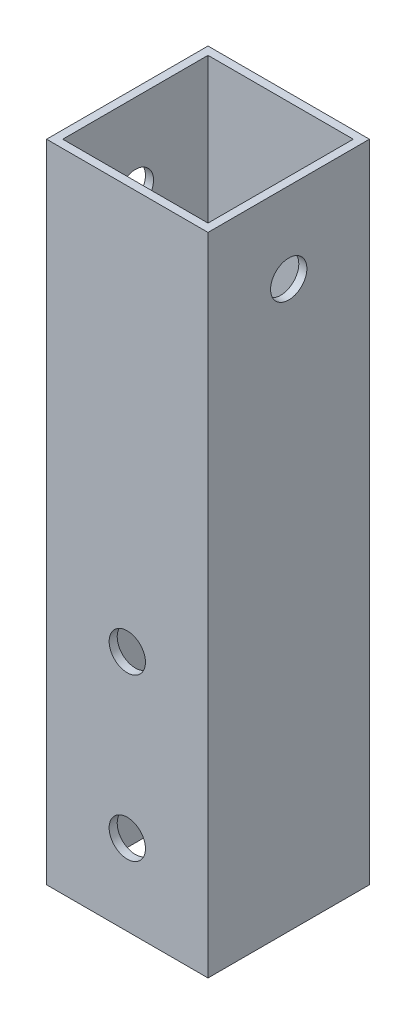
SolidWorks part; units mm, degrees
ref_plane "Front Plane" through (0, 0, 0) normal (0, 0, 1) x (1, 0, 0)
ref_plane "Top Plane" through (0, 0, 0) normal (0, 1, 0) x (1, 0, 0)
ref_plane "Right Plane" through (0, 0, 0) normal (1, 0, 0) x (0, 0, -1)
sketch "Sketch1" plane through (0, 0, 0) normal (0, 1, 0) x (1, 0, 0)
  line L0 (-9, -9) -> (-9, 9)
  line L1 (-10, -10) -> (10, -10)
  line L2 (-10, -10) -> (-10, 10)
  line L3 (-10, 10) -> (10, 10)
  line L4 (10, -10) -> (10, 10)
  line L5 (-10, -10) -> (10, 10) construction
  line L6 (-10, 10) -> (10, -10) construction
  line L7 (-9, 9) -> (9, 9)
  line L8 (9, -9) -> (9, 9)
  line L9 (-9, -9) -> (9, -9)
  point P0 (0, 0)
  dimension "D1" = 20
  dimension "D2" = 20
  dimension "D3" = 1
extrude "Boss-Extrude1" add sketch "Sketch1" along normal blind 80
sketch "Sketch2" plane through (0, 0, 10) normal (0, 0, 1) x (1, 0, 0)
  line L0 (-10, 0) -> (10, 0) construction
  circle A0 centre (0, 10) radius 2.25
  circle A1 centre (0, 30) radius 2.25
  dimension "D1" = 4.5
  dimension "D3" = 20
  dimension "D2" = 10
extrude "Cut-Extrude1" cut sketch "Sketch2" against normal through all
sketch "Sketch3" plane through (10, 0, 0) normal (1, 0, 0) x (0, 0, -1)
  line L0 (-10, 80) -> (10, 80) construction
  circle A0 centre (0, 70) radius 2.25
  dimension "D1" = 4.5
  dimension "D2" = 10
extrude "Cut-Extrude2" cut sketch "Sketch3" against normal through all
